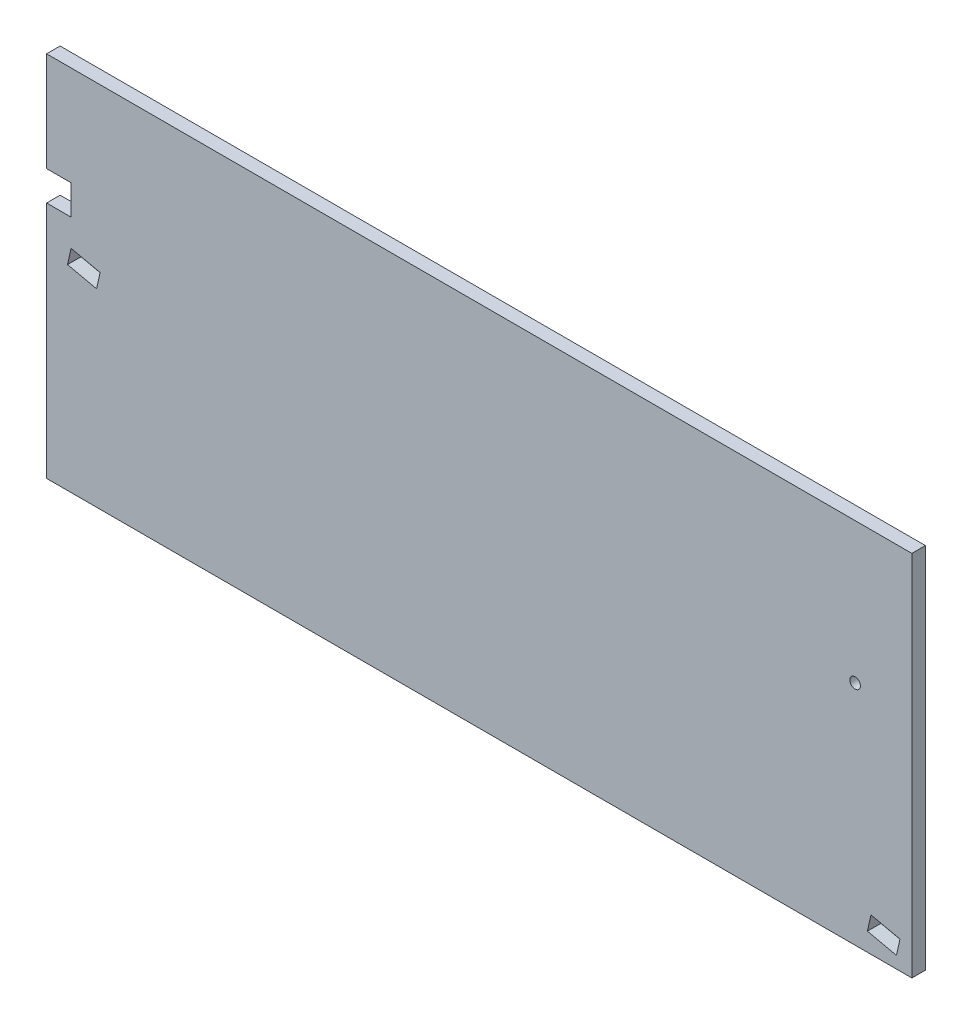
SolidWorks part; units mm, degrees
ref_plane "Front Plane" through (0, 0, 0) normal (0, 0, 1) x (1, 0, 0)
ref_plane "Top Plane" through (0, 0, 0) normal (0, 1, 0) x (1, 0, 0)
ref_plane "Right Plane" through (0, 0, 0) normal (1, 0, 0) x (0, 0, -1)
sketch "Sketch1" plane through (0, 0, 0) normal (0, 0, 1) x (1, 0, 0)
  line L0 (88.265, 53.34) -> (88.265, 86.36) construction
  line L1 (-101.6, 86.36) -> (101.6, 86.36)
  line L2 (-101.6, 86.36) -> (-101.6, 0)
  line L3 (-101.6, 0) -> (101.6, 0)
  line L4 (101.6, 86.36) -> (101.6, 0)
  circle A1 centre (88.265, 53.34) radius 1.25
  dimension "D3" = 2.5
  dimension "D1" = 53.34
  dimension "D2" = 13.335
  dimension "D4" = 86.36
  dimension "D5" = 203.2
extrude "Boss-Extrude1" add sketch "Sketch1" along normal blind 3.175
sketch "Sketch3" plane through (0, 0, 3.175) normal (0, 0, 1) x (1, 0, 0)
  line L0 (91.9866, 8.0255) -> (91.1619, 4.3058)
  line L1 (91.1619, 4.3058) -> (97.9814, 2.794)
  line L2 (97.9814, 2.794) -> (98.806, 6.5137)
  line L3 (98.806, 6.5137) -> (91.9866, 8.0255)
  line L4 (-101.6, 0) -> (101.6, 0) construction
  line L5 (101.6, 0) -> (101.6, 86.36) construction
  dimension "D1" = 2.794
  dimension "D2" = 2.794
  dimension "D3" = 12.5
  dimension "D4" = 3.81
  dimension "D5" = 6.985
extrude "Cut-Extrude1" cut sketch "Sketch3" against normal through all
pattern_linear "LPattern1" count 2 spacing 192.405 along (-0.9763, 0.2164, 0) of "Cut-Extrude1"
sketch "Sketch4" plane through (0, 0, 3.175) normal (0, 0, 1) x (1, 0, 0)
  line L0 (-95.8577, 49.6696) -> (-95.8577, 56.0196) construction
  line L1 (-95.8577, 56.0196) -> (-101.6, 56.0196)
  line L3 (-101.6, 86.36) -> (-101.6, 0) construction
  line L4 (-101.6, 56.0196) -> (-101.6, 63.0046)
  line L5 (-101.6, 63.0046) -> (-95.8577, 63.0046)
  line L6 (-95.8577, 63.0046) -> (-95.8577, 56.0196)
  dimension "D1" = 6.35
  dimension "D2" = 6.985
extrude "Cut-Extrude2" cut sketch "Sketch4" against normal through all
